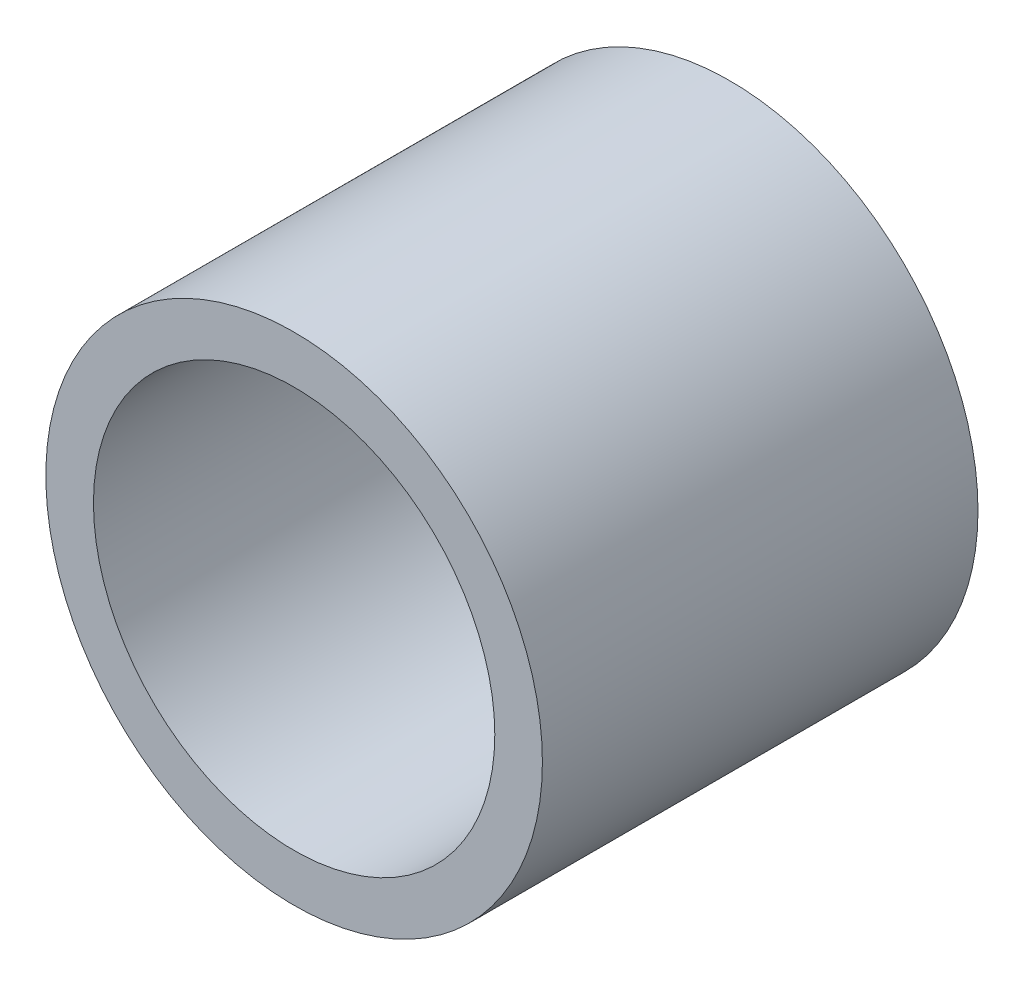
SolidWorks part; units mm, degrees
ref_plane "Front Plane" through (0, 0, 0) normal (0, 0, 1) x (1, 0, 0)
ref_plane "Top Plane" through (0, 0, 0) normal (0, 1, 0) x (1, 0, 0)
ref_plane "Right Plane" through (0, 0, 0) normal (1, 0, 0) x (0, 0, -1)
sketch "Adapter_8OD_6p45ID_profile" plane through (0, 0, 0) normal (0, 0, 1) x (1, 0, 0)
  circle A0 centre (0, 0) radius 3.99
  circle A1 centre (0, 0) radius 3.225
extrude "Adapter_8OD_6p45ID" add sketch "Adapter_8OD_6p45ID_profile" along normal blind 7
